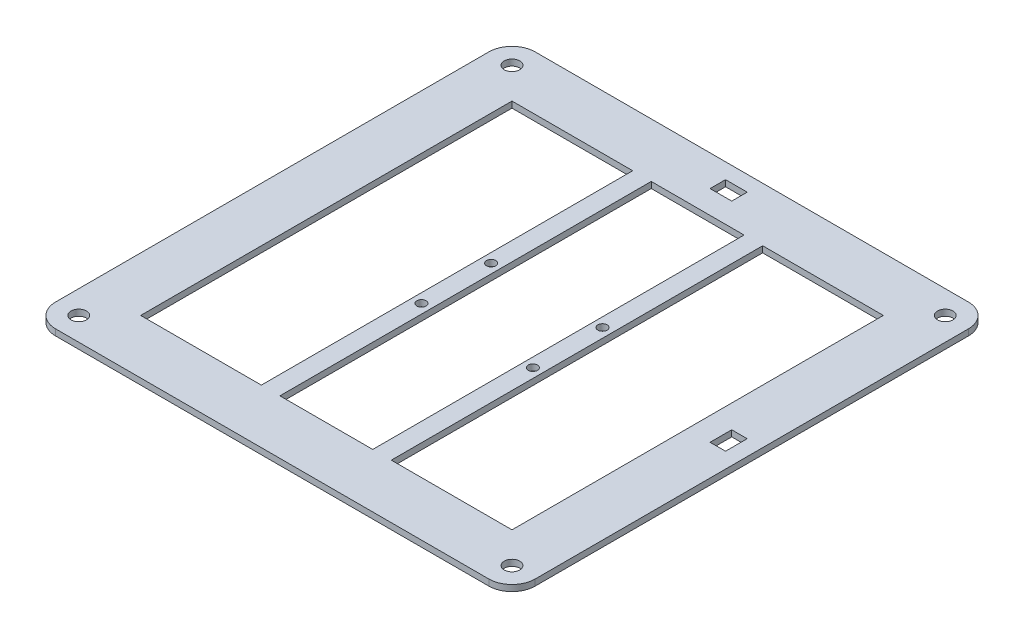
SolidWorks part; units mm, degrees
ref_plane "Alzado" through (0, 0, 0) normal (0, 0, 1) x (1, 0, 0)
ref_plane "Planta" through (0, 0, 0) normal (0, 1, 0) x (1, 0, 0)
ref_plane "Vista lateral" through (0, 0, 0) normal (1, 0, 0) x (0, 0, -1)
sketch "Croquis1" plane through (0, 0, 0) normal (0, 1, 0) x (1, 0, 0)
  line L0 (-10, -10) -> (-10, 150)
  line L1 (0, 0) -> (140, 0) construction
  line L2 (0, 0) -> (0, 140) construction
  line L3 (0, 140) -> (140, 140) construction
  line L4 (140, 0) -> (140, 140) construction
  line L5 (-10, 150) -> (150, 150)
  line L6 (150, -10) -> (150, 150)
  line L7 (-10, -10) -> (150, -10)
  line L8 (10, 10) -> (10, 130)
  line L9 (10, 130) -> (49, 130)
  line L10 (130, 10) -> (130, 130)
  line L11 (10, 10) -> (49, 10)
  line L12 (10, 70) -> (130, 70) construction
  line L13 (52, 70) -> (52, 81.25) construction
  line L14 (52, 70) -> (52, 58.75) construction
  line L15 (70, 70) -> (70, 160) construction
  line L16 (49, 147.7957) -> (55, 147.7957) construction
  line L18 (49, 130) -> (49, 10)
  line L20 (55, 130) -> (55, 10)
  line L21 (52, 147.7957) -> (52, 81.25) construction
  line L22 (55, 130) -> (85, 130)
  line L23 (55, 10) -> (85, 10)
  line L24 (10, 130) -> (130, 130) construction
  line L25 (85, 130) -> (85, 10)
  line L26 (10, 10) -> (130, 10) construction
  line L27 (91, 130) -> (91, 10)
  line L28 (91, 130) -> (130, 130)
  line L29 (91, 10) -> (130, 10)
  line L31 (137.5, 66.5) -> (142.5, 66.5)
  line L32 (137.5, 66.5) -> (137.5, 73.5)
  line L33 (137.5, 73.5) -> (142.5, 73.5)
  line L34 (142.5, 66.5) -> (142.5, 73.5)
  line L35 (137.5, 66.5) -> (142.5, 73.5) construction
  line L36 (137.5, 73.5) -> (142.5, 66.5) construction
  line L37 (66.5, 142.5) -> (73.5, 142.5)
  line L38 (66.5, 142.5) -> (66.5, 137.5)
  line L39 (66.5, 137.5) -> (73.5, 137.5)
  line L40 (73.5, 142.5) -> (73.5, 137.5)
  line L41 (66.5, 142.5) -> (73.5, 137.5) construction
  line L42 (66.5, 137.5) -> (73.5, 142.5) construction
  circle A0 centre (52, 81.25) radius 1.5
  circle A1 centre (52, 58.75) radius 1.5
  circle A2 centre (0, 140) radius 2.5
  circle A3 centre (0, 0) radius 2.5
  circle A4 centre (88, 81.25) radius 1.5
  circle A5 centre (88, 58.75) radius 1.5
  circle A6 centre (140, 0) radius 2.5
  circle A7 centre (140, 140) radius 2.5
  point P41 (140, 70)
  point P46 (70, 140)
  dimension "D4" = 3
  dimension "D8" = 5
  dimension "D1" = 140
  dimension "D2" = 10
  dimension "D5" = 18
  dimension "D6" = 11.25
  dimension "D7" = 6
  dimension "D9" = 5
  dimension "D10" = 7
  dimension "D3" = 10
extrude "Saliente-Extruir1" add sketch "Croquis1" along normal blind 2
sketch "Croquis2" plane through (0, 2, 0) normal (0, 1, 0) x (1, 0, 0)
  line L0 (0, 147.5) -> (140, 147.5)
  line L1 (147.5, 140) -> (147.5, 0)
  line L2 (140, -7.5) -> (0, -7.5)
  line L3 (-7.5, 0) -> (-7.5, 140)
  line L4 (-10, -10) -> (150, -10)
  line L5 (150, -10) -> (150, 150)
  line L6 (150, 150) -> (-10, 150)
  line L7 (-10, 150) -> (-10, -10)
  line L8 (-10, -10) -> (150, -10)
  line L9 (150, -10) -> (150, 150)
  line L10 (150, 150) -> (-10, 150)
  line L11 (-10, 150) -> (-10, -10)
  line L12 (-7.5, 150) -> (-7.5, 150.2937)
  arc A0 (0, 147.5) -> (-7.5, 140) centre (0, 140) ccw
  arc A1 (147.5, 140) -> (140, 147.5) centre (140, 140) ccw
  arc A2 (140, -7.5) -> (147.5, 0) centre (140, 0) ccw
  arc A3 (-7.5, 0) -> (0, -7.5) centre (0, 0) ccw
  line M17 (-10, -10) -> (150, -10)
  line M18 (150, -10) -> (150, 150)
  line M19 (150, 150) -> (-10, 150)
  line M20 (-10, 150) -> (-10, -10)
  dimension "D2" = 15
  dimension "D1" = 0
extrude "Cortar-Extruir1" cut sketch "Croquis2" against normal blind 10 contours L10 A3 L3 A0 L0 A1 L1 A2 L2 M20 M17 M18 M19
